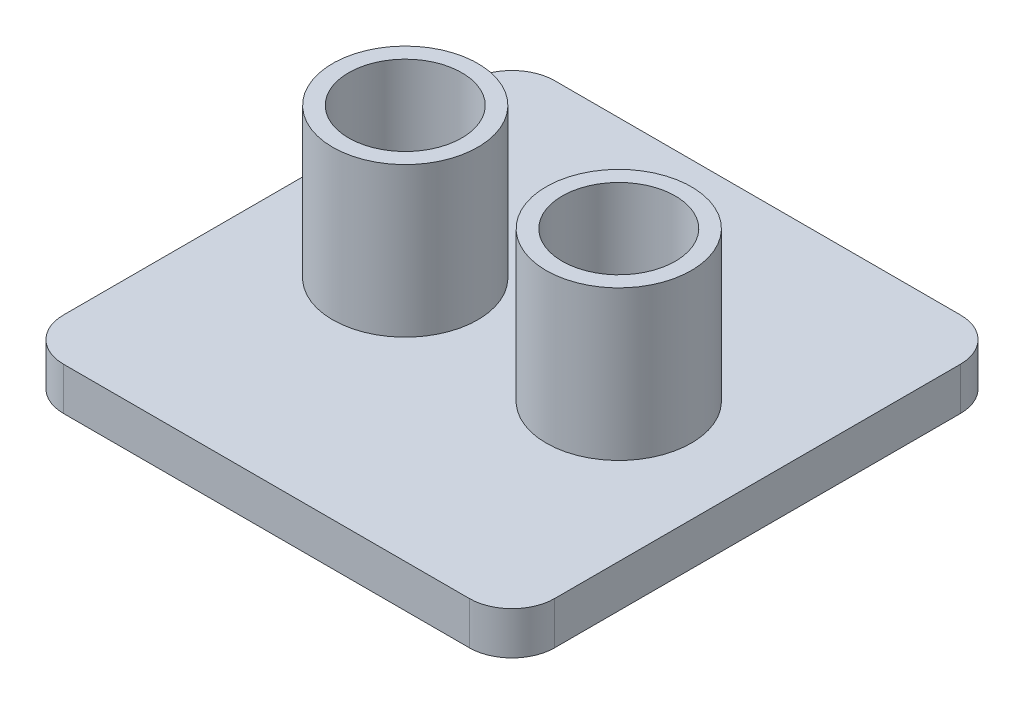
SolidWorks part; units mm, degrees
ref_plane "Front Plane" through (0, 0, 0) normal (0, 0, 1) x (1, 0, 0)
ref_plane "Top Plane" through (0, 0, 0) normal (0, 1, 0) x (1, 0, 0)
ref_plane "Right Plane" through (0, 0, 0) normal (1, 0, 0) x (0, 0, -1)
sketch "Sketch1" plane through (0, 0, 0) normal (0, 1, 0) x (1, 0, 0)
  line L1 (-9.5, -11.5) -> (9.5, -11.5)
  line L2 (-11.5, -9.5) -> (-11.5, 9.5)
  line L3 (-9.5, 11.5) -> (9.5, 11.5)
  line L4 (11.5, -9.5) -> (11.5, 9.5)
  line L5 (-11.5, -11.5) -> (11.5, 11.5) construction
  line L6 (-11.5, 11.5) -> (11.5, -11.5) construction
  arc A0 (-11.5, -9.5) -> (-9.5, -11.5) centre (-9.5, -9.5) ccw
  arc A1 (11.5, -9.5) -> (9.5, -11.5) centre (9.5, -9.5) cw
  arc A2 (11.5, 9.5) -> (9.5, 11.5) centre (9.5, 9.5) ccw
  arc A3 (-9.5, 11.5) -> (-11.5, 9.5) centre (-9.5, 9.5) ccw
  point P0 (0, 0)
  dimension "D3" = 2
  dimension "D1" = 23
  dimension "D2" = 23
extrude "Boss-Extrude1" add sketch "Sketch1" along normal blind 2
sketch "Sketch2" plane through (0, 2, 0) normal (0, 1, 0) x (1, 0, 0)
  line L0 (-5, 0) -> (5, 0) construction
  circle A0 centre (-5, 0) radius 3.4
  circle A1 centre (5, 0) radius 3.4
  point P4 (0, 0)
  dimension "D2" = 6.8
  dimension "D3" = 6.8
  dimension "D1" = 10
extrude "Boss-Extrude2" add sketch "Sketch2" along normal blind 7
sketch "Sketch3" plane through (0, 9, 0) normal (0, 1, 0) x (1, 0, 0)
  line L0 (-5, 0) -> (5, 0) construction
  circle A0 centre (-5, 0) radius 2.65
  circle A1 centre (5, 0) radius 2.65
  point P4 (0, 0)
  dimension "D1" = 10
  dimension "D2" = 5.3
  dimension "D3" = 5.3
extrude "Cut-Extrude1" cut sketch "Sketch3" against normal through all
equation "\"D2@Sketch1\"=\"D1@Sketch1\""
equation "\"D3@Sketch2\"=\"D2@Sketch2\""
equation "\"D3@Sketch3\"=\"D2@Sketch3\""
equation "\"D1@Sketch3\"=\"D1@Sketch2\""
equation "\"D2@Sketch3\"=\"D2@Sketch2\"-1.5"
